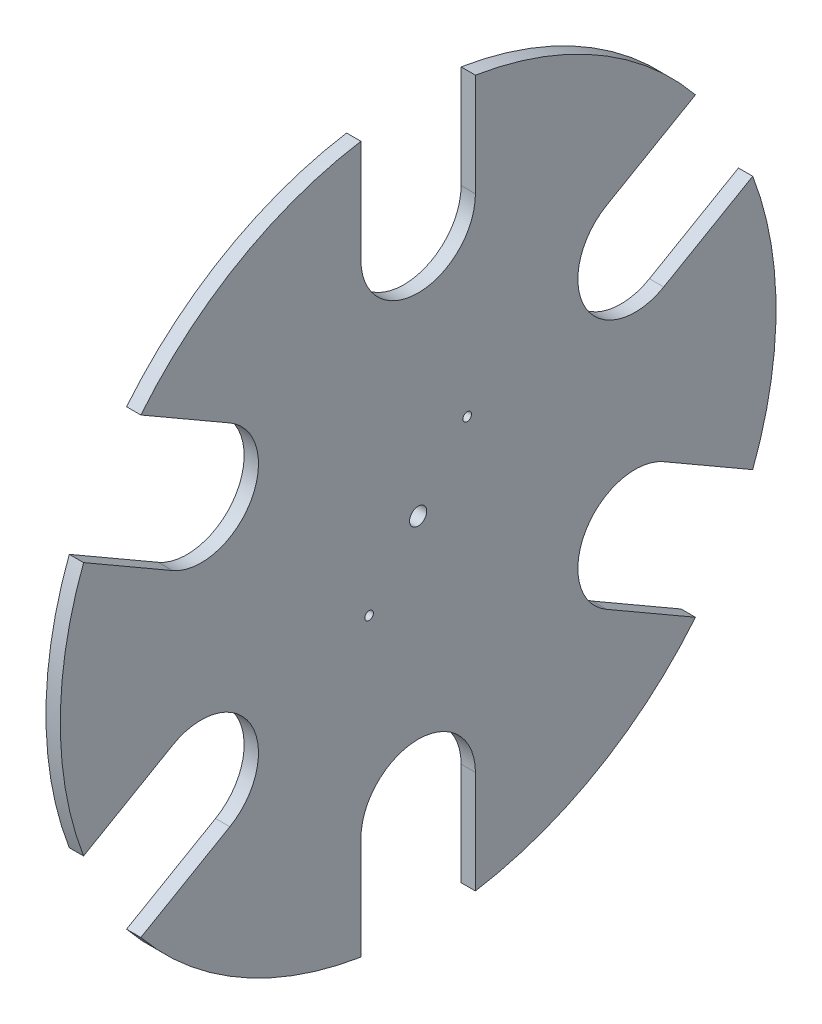
SolidWorks part; units mm, degrees
material "AISI 304"
ref_plane "Front Plane" through (0, 0, 0) normal (0, 0, 1) x (1, 0, 0)
ref_plane "Top Plane" through (0, 0, 0) normal (0, 1, 0) x (1, 0, 0)
ref_plane "Right Plane" through (0, 0, 0) normal (1, 0, 0) x (0, 0, -1)
sketch "Sketch1" plane through (0, 0, 0) normal (1, 0, 0) x (0, 0, -1)
  line L0 (0, 0) -> (0, 250) construction
  line L1 (0, 0) -> (216.5064, 125) construction
  line L2 (0, 0) -> (216.5064, -125) construction
  line L3 (0, 0) -> (0, -250) construction
  line L4 (0, 0) -> (-216.5064, -125) construction
  line L5 (0, 0) -> (-216.5064, 125) construction
  circle A0 centre (0, 0) radius 250
  circle A1 centre (0, 0) radius 6
  circle A2 centre (0, 175) radius 40
  circle A3 centre (151.5544, 87.5) radius 40
  circle A4 centre (151.5544, -87.5) radius 40
  circle A5 centre (0, -175) radius 40
  circle A6 centre (-151.5544, -87.5) radius 40
  circle A7 centre (-151.5544, 87.5) radius 40
  point P13 (0, 0)
  point P26 (0, 0)
  dimension "D1" = 500
  dimension "D2" = 12
  dimension "D4" = 80
  dimension "D5" = 175
  dimension "D3" = 6
  dimension "D6" = 6
extrude "Boss-Extrude1" add sketch "Sketch1" along normal blind 10
ref_plane "Plane1" through (10, 0, 0) normal (-1, 0, 0) x (0, 0, 1)
sketch "Sketch2" plane through (0, 0, 0) normal (-1, 0, 0) x (0, 0, 1)
  line L0 (-40, 175) -> (-40, 246.7793)
  line L1 (40, 175) -> (40, 246.7793)
  line L2 (131.5544, 122.141) -> (193.7171, 158.0306)
  line L3 (171.5544, 52.859) -> (233.7171, 88.7486)
  line L4 (171.5544, -52.859) -> (233.7171, -88.7486)
  line L5 (131.5544, -122.141) -> (193.7171, -158.0306)
  line L6 (40, -175) -> (40, -246.7793)
  line L7 (-40, -175) -> (-40, -246.7793)
  line L8 (-131.5544, -122.141) -> (-193.7171, -158.0306)
  line L9 (-171.5544, -52.859) -> (-233.7171, -88.7486)
  line L10 (-171.5544, 52.859) -> (-233.7171, 88.7486)
  line L11 (-131.5544, 122.141) -> (-193.7171, 158.0306)
  circle A0 centre (0, 175) radius 40 construction
  circle A1 centre (0, 0) radius 250 construction
  arc A2 (-40, 175) -> (40, 175) centre (0, 175) cw
  arc A3 (-40, 246.7793) -> (40, 246.7793) centre (0, 0) cw
  arc A4 (131.5544, 122.141) -> (171.5544, 52.859) centre (151.5544, 87.5) cw
  arc A5 (193.7171, 158.0306) -> (233.7171, 88.7486) centre (0, 0) cw
  arc A6 (171.5544, -52.859) -> (131.5544, -122.141) centre (151.5544, -87.5) cw
  arc A7 (233.7171, -88.7486) -> (193.7171, -158.0306) centre (0, 0) cw
  arc A8 (40, -175) -> (-40, -175) centre (0, -175) cw
  arc A9 (40, -246.7793) -> (-40, -246.7793) centre (0, 0) cw
  arc A10 (-131.5544, -122.141) -> (-171.5544, -52.859) centre (-151.5544, -87.5) cw
  arc A11 (-193.7171, -158.0306) -> (-233.7171, -88.7486) centre (0, 0) cw
  arc A12 (-171.5544, 52.859) -> (-131.5544, 122.141) centre (-151.5544, 87.5) cw
  arc A13 (-233.7171, 88.7486) -> (-193.7171, 158.0306) centre (0, 0) cw
  circle A14 centre (-34.2487, 43.0352) radius 3
  circle A15 centre (34.2487, -43.0352) radius 3
  point P52 (0, 0)
  dimension "D1" = 6
extrude "Cut-Extrude1" cut sketch "Sketch2" against normal through all both and the other way through all
